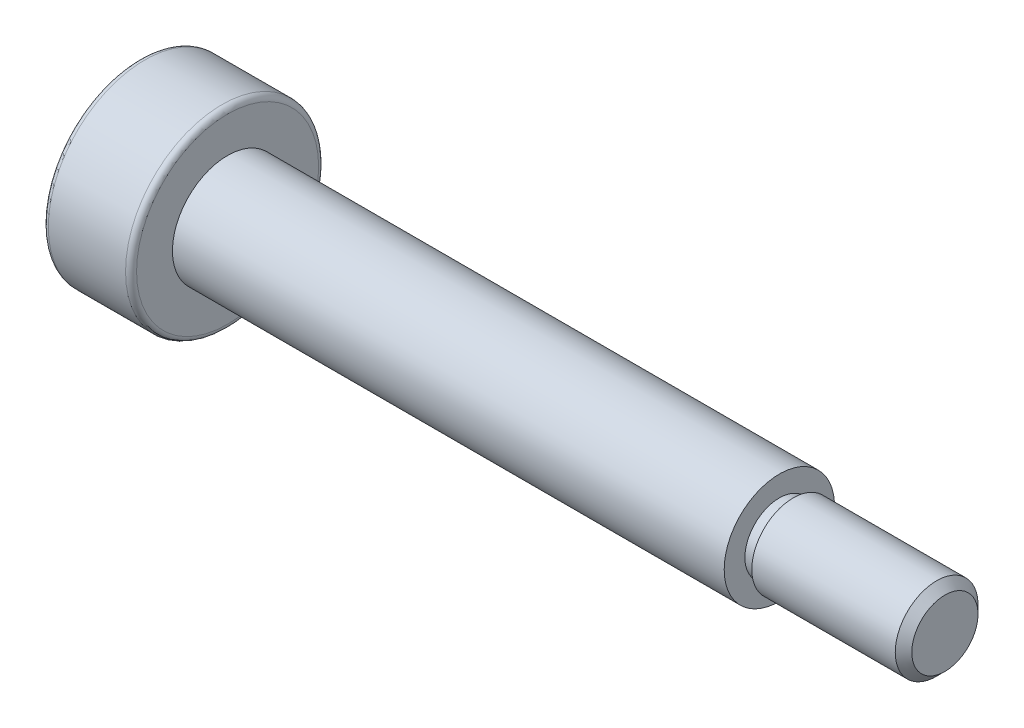
SolidWorks part; units mm, degrees
ref_plane "前视基准面" through (0, 0, 0) normal (0, 0, 1) x (1, 0, 0)
ref_plane "上视基准面" through (0, 0, 0) normal (0, 1, 0) x (1, 0, 0)
ref_plane "右视基准面" through (0, 0, 0) normal (1, 0, 0) x (0, 0, -1)
sketch "草图1" plane through (0, 0, 0) normal (0, 0, 1) x (1, 0, 0)
  line L0 (-14.6, 0) -> (14.6, 0) construction
  line L1 (-14.6, 0) -> (-14.6, 3.5)
  line L2 (-14.6, 3.5) -> (-11.4, 3.5)
  line L3 (-11.4, 3.5) -> (-11.4, 2)
  line L4 (-11.4, 2) -> (8.6, 2)
  line L5 (8.6, 2) -> (8.6, 1.5)
  line L6 (8.6, 1.5) -> (14.6, 1.5)
  line L7 (14.6, 1.5) -> (14.6, 0)
  line L8 (-14.6, 0) -> (14.6, 0)
  dimension "D1" = 4
  dimension "D2" = 7
  dimension "D3" = 3
  dimension "D4" = 6
  dimension "D5" = 20
  dimension "D6" = 3.2
revolve "旋转1" add sketch "草图1" angle 360 about L0
fillet "圆角1" radius 0.2 2 edges at (-11.4, 0, 3.5) (-14.6, 0, 3.5)
chamfer "倒角1" distance 0.3 angle 45 1 edges at (14.6, 0, 1.5)
sketch "草图3" plane through (0, 0, 0) normal (0, 0, 1) x (1, 0, 0)
  line L0 (8.6, 0) -> (14.3, 0) construction
  line L1 (8.6, -1.5) -> (8.6, 1.5) construction
  line L2 (14.3, 1.5) -> (14.3, -1.5) construction
  line L3 (8.6, -2) -> (8.6, 2) construction
  line L4 (8.6, 1.5) -> (9.1, 1.5)
  line L5 (8.6, 1.5) -> (8.6, 1.25)
  line L6 (8.6, 1.25) -> (9.1, 1.25)
  line L7 (9.1, 1.5) -> (9.1, 1.25)
  line L8 (14.3, 1.5) -> (8.6, 1.5) construction
  dimension "D1" = 2.5
  dimension "D2" = 0.5
revolve "切除-旋转1" cut sketch "草图3" angle 360 about L0
sketch "草图4" plane through (-14.6, 0, 0) normal (-1, 0, 0) x (0, 0, 1)
  line L1 (1.7321, 0) -> (0.866, 1.5)
  line L2 (0.866, 1.5) -> (-0.866, 1.5)
  line L3 (-0.866, 1.5) -> (-1.7321, 0)
  line L4 (-1.7321, 0) -> (-0.866, -1.5)
  line L5 (-0.866, -1.5) -> (0.866, -1.5)
  line L6 (0.866, -1.5) -> (1.7321, 0)
  circle A0 centre (0, 0) radius 1.5 construction
  dimension "D1" = 3
extrude "切除-拉伸1" cut sketch "草图4" against normal blind 2
